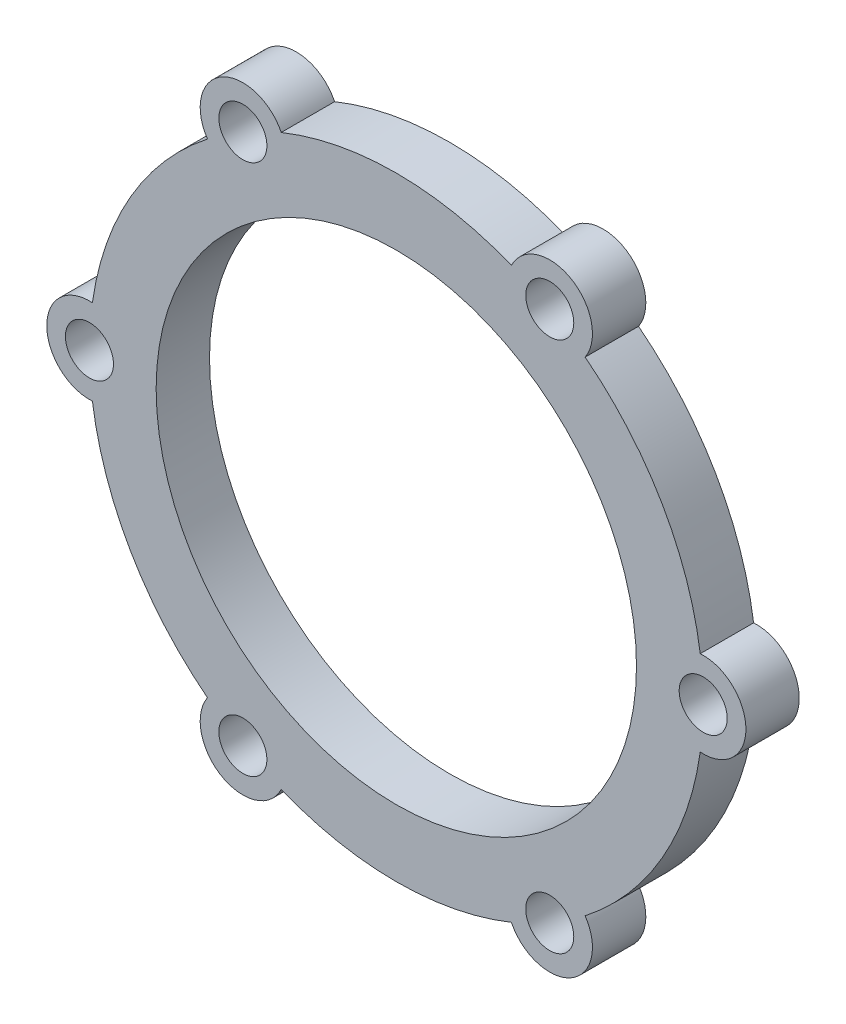
SolidWorks part; units mm, degrees
ref_plane "Front Plane" through (0, 0, 0) normal (0, 0, 1) x (1, 0, 0)
ref_plane "Top Plane" through (0, 0, 0) normal (0, 1, 0) x (1, 0, 0)
ref_plane "Right Plane" through (0, 0, 0) normal (1, 0, 0) x (0, 0, -1)
sketch "Sketch1" plane through (0, 0, 0) normal (0, 0, 1) x (1, 0, 0)
  line L0 (-500, -866.0254) -> (24500, 42435.2448) construction
  arc A0 (-35.3832, 45.3242) -> (-56.9435, 7.9806) centre (0, 0) ccw
  circle A1 centre (0, 0) radius 45
  arc A2 (35.3832, 45.3242) -> (21.5603, 53.3048) centre (28.75, 49.7965) ccw
  circle A3 centre (28.75, 49.7965) radius 4.5
  arc A4 (56.9435, -7.9806) -> (56.9435, 7.9806) centre (57.5, 0) ccw
  circle A5 centre (57.5, 0) radius 4.5
  arc A6 (21.5603, -53.3048) -> (35.3832, -45.3242) centre (28.75, -49.7965) ccw
  circle A7 centre (28.75, -49.7965) radius 4.5
  arc A8 (-35.3832, -45.3242) -> (-21.5603, -53.3048) centre (-28.75, -49.7965) ccw
  circle A9 centre (-28.75, -49.7965) radius 4.5
  arc A10 (-56.9435, 7.9806) -> (-56.9435, -7.9806) centre (-57.5, 0) ccw
  circle A11 centre (-57.5, 0) radius 4.5
  arc A12 (-21.5603, 53.3048) -> (-35.3832, 45.3242) centre (-28.75, 49.7965) ccw
  circle A13 centre (-28.75, 49.7965) radius 4.5
  arc A14 (21.5603, 53.3048) -> (-21.5603, 53.3048) centre (0, 0) ccw
  arc A15 (56.9435, 7.9806) -> (35.3832, 45.3242) centre (0, 0) ccw
  arc A16 (35.3832, -45.3242) -> (56.9435, -7.9806) centre (0, 0) ccw
  arc A17 (-56.9435, -7.9806) -> (-35.3832, -45.3242) centre (0, 0) ccw
  arc A18 (-32.5561, -47.3957) -> (-24.7678, -51.8922) centre (0, 0) ccw
  arc A19 (-21.5603, -53.3048) -> (21.5603, -53.3048) centre (0, 0) ccw
  point P26 (0, 0)
  dimension "D1" = 115
  dimension "D2" = 90
  dimension "D3" = 16
  dimension "D4" = 9
  dimension "D5" = 6
extrude "Boss-Extrude1" add sketch "Sketch1" along normal blind 10 contours A8 L0 A9 A1 A3 A2 A14 A12 A0 A10 A17 A13 A11 | L0 A8 A19 A6 A16 A4 A15 A2 A3 A1 A9 A5 A7
